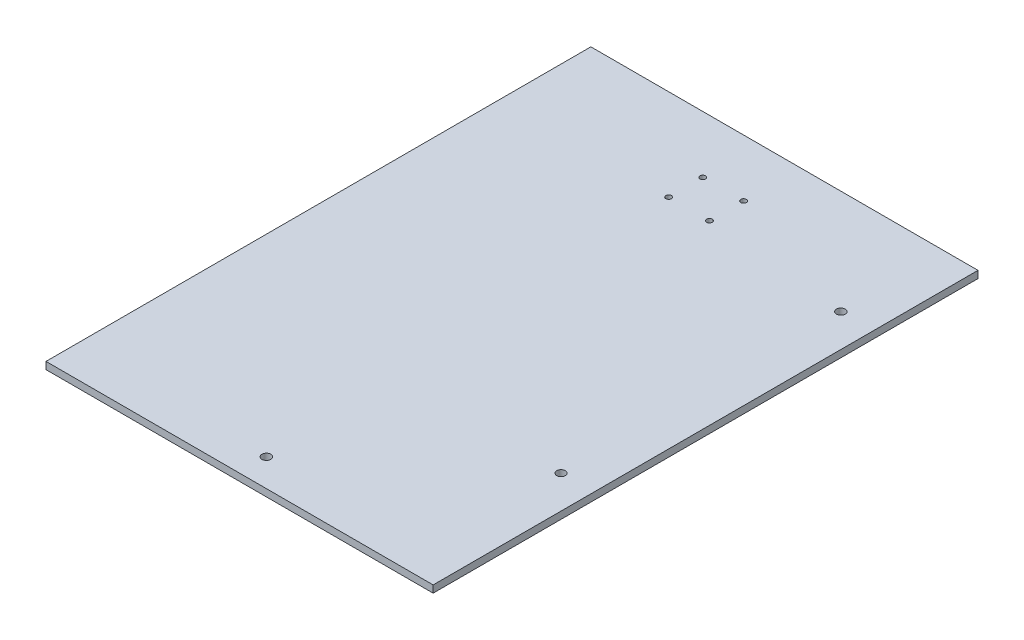
SolidWorks part; units mm, degrees
material "2024-T361"
ref_plane "Front Plane" through (0, 0, 0) normal (0, 0, 1) x (1, 0, 0)
ref_plane "Top Plane" through (0, 0, 0) normal (0, 1, 0) x (1, 0, 0)
ref_plane "Right Plane" through (0, 0, 0) normal (1, 0, 0) x (0, 0, -1)
sketch "Sketch1" plane through (0, 0, 0) normal (0, 0, 1) x (1, 0, 0)
  line L0 (5, -60) -> (5, 85) construction
  line L1 (5, 45) -> (275, 45)
  line L2 (5, 45) -> (5, 50)
  line L3 (5, 50) -> (275, 50)
  line L4 (275, 45) -> (275, 50)
  line L5 (275, -60) -> (275, 85) construction
  line L7 (3, -65) -> (277, -65) construction
  dimension "D1" = 5
  dimension "D2" = 110
extrude "Boss-Extrude1" add sketch "Sketch1" along normal blind 380
sketch "Sketch6" plane through (0, 45, 0) normal (0, -1, 0) x (1, 0, 0)
  circle A0 centre (122.9011, 39.847) radius 1.9331
  circle A1 centre (122.9011, 63.6657) radius 1.9376
  circle A2 centre (151.3623, 39.847) radius 1.9381
  circle A3 centre (151.3623, 63.6657) radius 1.9625
extrude "Cut-Extrude1" cut sketch "Sketch6" against normal up to next
sketch "Sketch7" plane through (0, 50, 0) normal (0, 1, 0) x (1, 0, 0)
  circle A0 centre (252.1123, -267.8897) radius 3.0185
  circle A1 centre (252.1123, -72.7488) radius 3.0894
  circle A2 centre (139.4673, -360.7759) radius 3.1062
  point P4 (158.9236, -360.7759)
  point P5 (124.6679, -360.7759)
  point P8 (139.4673, -360.7759)
extrude "Cut-Extrude2" cut sketch "Sketch7" against normal up to next
